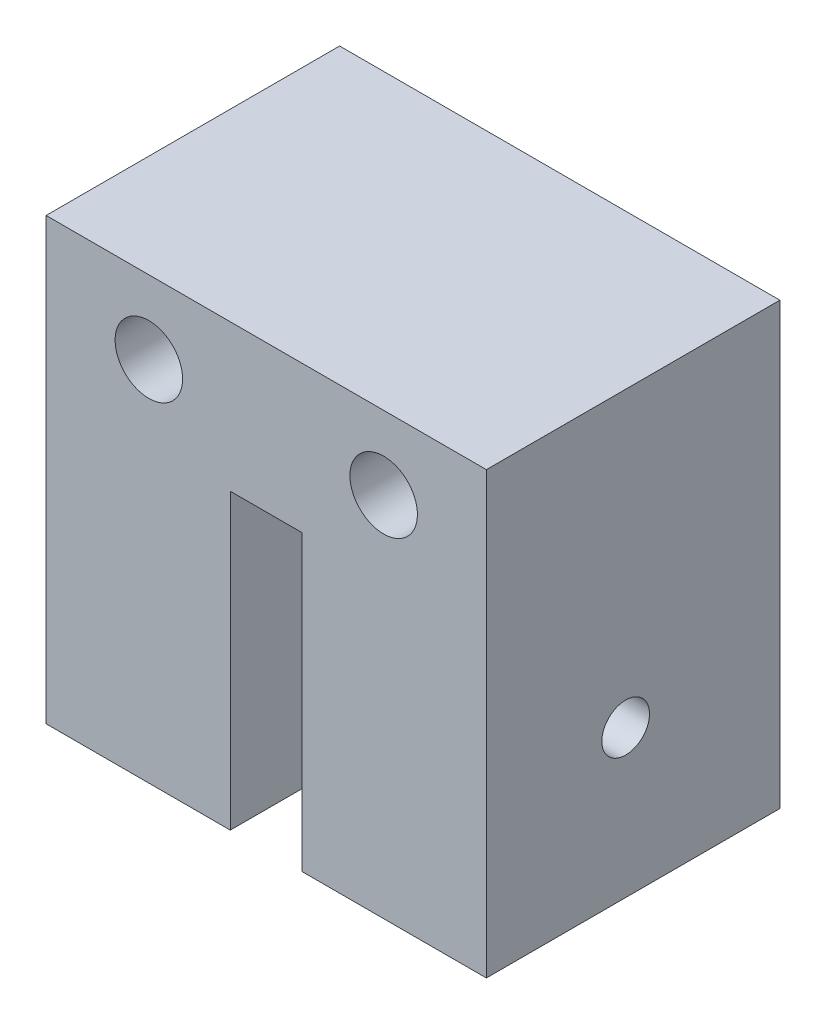
SolidWorks part; units mm, degrees
ref_plane "Front Plane" through (0, 0, 0) normal (0, 0, 1) x (1, 0, 0)
ref_plane "Top Plane" through (0, 0, 0) normal (0, 1, 0) x (1, 0, 0)
ref_plane "Right Plane" through (0, 0, 0) normal (1, 0, 0) x (0, 0, -1)
sketch "Sketch1" plane through (0, 0, 0) normal (0, 1, 0) x (1, 0, 0)
  line L1 (-15, -10) -> (15, -10)
  line L2 (-15, -10) -> (-15, 10)
  line L3 (-15, 10) -> (15, 10)
  line L4 (15, -10) -> (15, 10)
  line L5 (-15, -10) -> (15, 10) construction
  line L6 (-15, 10) -> (15, -10) construction
  point P0 (0, 0)
  dimension "D1" = 30
  dimension "D2" = 20
extrude "Boss-Extrude1" add sketch "Sketch1" along normal blind 10
sketch "Sketch3" plane through (0, 0, 0) normal (0, -1, 0) x (1, 0, 0)
  line L0 (-15, 10) -> (15, 10) construction
  line L1 (-15, 10) -> (-2.45, 10)
  line L2 (-15, 10) -> (-15, -10)
  line L3 (-15, -10) -> (-2.45, -10)
  line L4 (-2.45, 10) -> (-2.45, -10)
  line L5 (15, -10) -> (-15, -10) construction
  line L6 (-15, -10) -> (-15, 10) construction
  line L7 (2.45, 10) -> (15, 10)
  line L8 (2.45, 10) -> (2.45, -10)
  line L9 (2.45, -10) -> (15, -10)
  line L10 (15, 10) -> (15, -10)
  line L11 (15, 10) -> (15, -10) construction
  line L12 (2.45, 10) -> (15, 10)
  line L13 (2.45, -10) -> (15, -10)
  line M1 (15, -10) -> (15, 10)
  line M2 (15, 10) -> (-15, 10)
  line M3 (-15, 10) -> (-15, -10)
  line M4 (-15, -10) -> (15, -10)
  dimension "D1" = 12.55
  dimension "D2" = 12.55
  dimension "D3" = 0
  dimension "D4" = 0
extrude "Boss-Extrude3" add sketch "Sketch3" along normal blind 20 contours L8 M2 M4 M1 | L4 M2 M3 M4
sketch "Sketch6" plane through (0, 0, -10) normal (0, 0, -1) x (-1, 0, 0)
  line L0 (15, 10) -> (15, -20) construction
  line L1 (-15, 10) -> (-15, -20) construction
  line L2 (15, 10) -> (-15, 10) construction
  line L3 (-15, 10) -> (15, 10) construction
  circle A0 centre (8, 5) radius 2.3
  circle A1 centre (-8, 5) radius 2.3
  dimension "D5" = 4.6
  dimension "D6" = 4.6
  dimension "D1" = 7
  dimension "D2" = 7
  dimension "D3" = 5
  dimension "D4" = 5
extrude "Cut-Extrude1" cut sketch "Sketch6" against normal through all
extrude "Cut-Extrude2" cut sketch "Sketch7" against normal through all
sketch "Sketch7" plane through (-15, -86.4203, -87.9466) normal (-1, 0, 0) x (0, 1, 0)
  circle A3 centre (76.4543, -88.4555) radius 1.625
